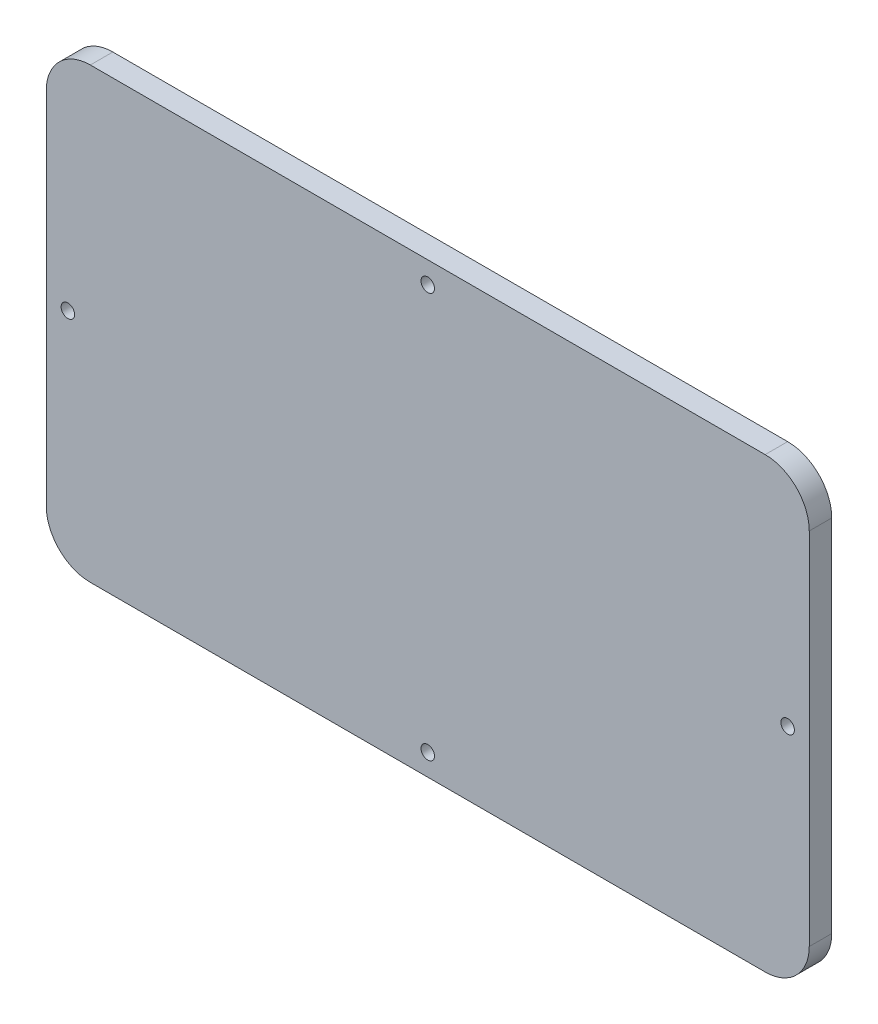
SolidWorks part; units mm, degrees
ref_plane "Plano frontal" through (0, 0, 0) normal (0, 0, 1) x (1, 0, 0)
ref_plane "Plano superior" through (0, 0, 0) normal (0, 1, 0) x (1, 0, 0)
ref_plane "Plano direito" through (0, 0, 0) normal (1, 0, 0) x (0, 0, -1)
sketch "Esboço1" plane through (0, 0, 0) normal (0, 0, 1) x (1, 0, 0)
  line L0 (75, 49.8) -> (-75, 49.8)
  line L1 (75, -50) -> (-75, -50)
  line L2 (85, -40) -> (85, 40)
  line L3 (75, 50) -> (-75, 50)
  line L4 (-85, -40) -> (-85, 40)
  line L5 (85, -50) -> (-85, 50) construction
  line L6 (85, 50) -> (-85, -50) construction
  line L7 (-84.8, -40) -> (-84.8, 40)
  line L8 (75, -49.8) -> (-75, -49.8)
  line L9 (84.8, -40) -> (84.8, 40)
  line L10 (0, 0) -> (0, 45) construction
  line L11 (0, 0) -> (80, 0) construction
  arc A0 (-75, -50) -> (-85, -40) centre (-75, -40) cw
  arc A1 (75, -50) -> (85, -40) centre (75, -40) ccw
  arc A2 (85, 40) -> (75, 50) centre (75, 40) ccw
  arc A3 (-75, 50) -> (-85, 40) centre (-75, 40) ccw
  arc A4 (-75, 49.8) -> (-84.8, 40) centre (-75, 40) ccw
  arc A5 (-75, -49.8) -> (-84.8, -40) centre (-75, -40) cw
  arc A6 (75, -49.8) -> (84.8, -40) centre (75, -40) ccw
  arc A7 (84.8, 40) -> (75, 49.8) centre (75, 40) ccw
  circle A8 centre (0, 45) radius 1.5
  circle A9 centre (80, 0) radius 1.5
  circle A10 centre (0, -45) radius 1.5
  circle A11 centre (-80, 0) radius 1.5
  point P0 (0, 0)
  dimension "D3" = 10
  dimension "D7" = 3
  dimension "D8" = 3
  dimension "D1" = 170
  dimension "D2" = 100
  dimension "D5" = 80
  dimension "D6" = 45
  dimension "D4" = 0.2
extrude "Ressalto-extrusão1" add sketch "Esboço1" along normal blind 5 contours L9 A7 L0 A4 L7 A5 L8 A6 A10 A9 A8 A11
